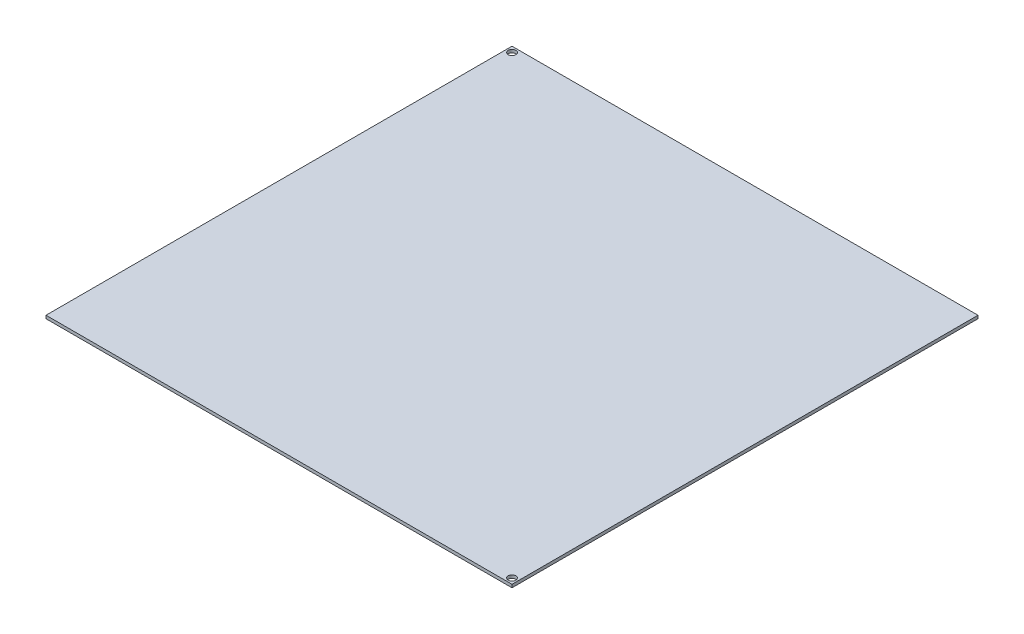
SolidWorks part; units mm, degrees
ref_plane "Front Plane" through (0, 0, 0) normal (0, 0, 1) x (1, 0, 0)
ref_plane "Top Plane" through (0, 0, 0) normal (0, 1, 0) x (1, 0, 0)
ref_plane "Right Plane" through (0, 0, 0) normal (1, 0, 0) x (0, 0, -1)
sketch "Sketch1" plane through (0, 0, 0) normal (0, 1, 0) x (1, 0, 0)
  line L1 (0, 0) -> (213, 0)
  line L2 (0, 0) -> (0, 213)
  line L3 (0, 213) -> (213, 213)
  line L4 (213, 0) -> (213, 213)
  line L5 (0, 0) -> (213, 213) construction
  line L6 (0, 213) -> (213, 0) construction
  point P4 (106.5, 106.5)
  dimension "D1" = 213
  dimension "D2" = 213
extrude "Boss-Extrude1" add sketch "Sketch1" along normal blind 1.4
sketch "Sketch2" plane through (0, 1.4, 0) normal (0, 1, 0) x (1, 0, 0)
  line L0 (0, 213) -> (213, 0) construction
  circle A0 centre (2.4996, 210.5004) radius 1.75
  circle A1 centre (210.5022, 2.4978) radius 1.75
  dimension "D1" = 3.5
  dimension "D2" = 3.5
  dimension "D3" = 294.16
  dimension "D4" = 3.535
extrude "Cut-Extrude1" cut sketch "Sketch2" against normal through all
